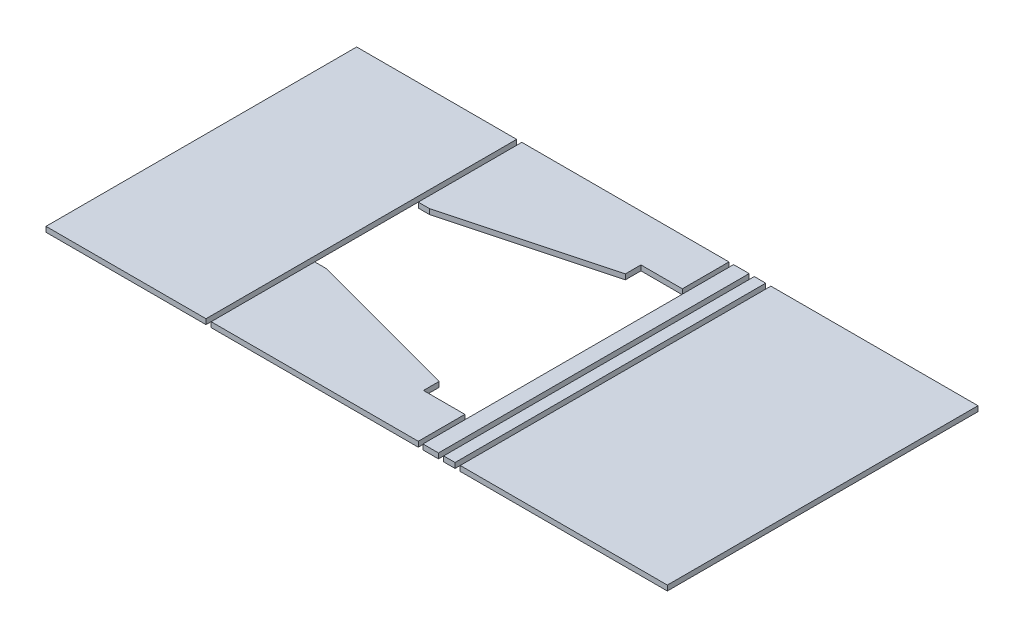
SolidWorks part; units mm, degrees
ref_plane "Front Plane" through (0, 0, 0) normal (0, 0, 1) x (1, 0, 0)
ref_plane "Top Plane" through (0, 0, 0) normal (0, 1, 0) x (1, 0, 0)
ref_plane "Right Plane" through (0, 0, 0) normal (1, 0, 0) x (0, 0, -1)
sketch "Sketch1" plane through (0, 0, 0) normal (0, 1, 0) x (1, 0, 0)
  line L0 (719, 90) -> (639, 90)
  line L33 (0, 0) -> (1200, 0)
  line L34 (0, 0) -> (0, 600)
  line L35 (0, 600) -> (1200, 600)
  line L36 (1200, 0) -> (1200, 600)
  line L37 (0, 0) -> (309, 0)
  line L38 (0, 0) -> (0, 600)
  line L39 (0, 600) -> (309, 600)
  line L40 (309, 0) -> (309, 600)
  line L41 (319, 600) -> (719, 600)
  line L42 (319, 600) -> (319, 400)
  line L43 (319, 400) -> (719, 400)
  line L44 (719, 600) -> (719, 400)
  line L45 (319, 0) -> (719, 0)
  line L46 (319, 0) -> (319, 200)
  line L47 (319, 200) -> (719, 200)
  line L48 (719, 0) -> (719, 200)
  line L49 (1200, 600) -> (800, 600)
  line L50 (1200, 600) -> (1200, 0)
  line L51 (1200, 0) -> (800, 0)
  line L52 (800, 600) -> (800, 0)
  line L53 (639, 90) -> (639, 120)
  line L54 (639, 120) -> (340.4359, 200)
  line L55 (719, 510) -> (639, 510)
  line L56 (790, 0) -> (768, 0)
  line L57 (790, 0) -> (790, 600)
  line L58 (790, 600) -> (768, 600)
  line L59 (768, 0) -> (768, 600)
  line L60 (758, 600) -> (728, 600)
  line L61 (758, 600) -> (758, 0)
  line L62 (758, 0) -> (728, 0)
  line L63 (728, 600) -> (728, 0)
  line L64 (639, 510) -> (639, 480)
  line L65 (639, 480) -> (340.4359, 400)
  dimension "D1" = 600
  dimension "D2" = 1200
  dimension "D3" = 309
  dimension "D4" = 200
  dimension "D5" = 200
  dimension "D6" = 10
  dimension "D7" = 10
  dimension "D8" = 400
  dimension "D9" = 400
  dimension "D10" = 400
  dimension "D11" = 15
  dimension "D12" = 80
  dimension "D13" = 30
  dimension "D14" = 90
  dimension "D15" = 10
  dimension "D16" = 22
  dimension "D17" = 10
  dimension "D18" = 30
  dimension "D19" = 90
  dimension "D20" = 30
  dimension "D21" = 15
  dimension "D22" = 80
extrude "Boss-Extrude1" add sketch "Sketch1" along normal blind 10 contours L33 L40 L35 L34 | L65 L64 L55 L44 L35 L42 L43 | L35 L52 L33 L36 | L53 L54 L47 L46 L33 L48 L0 | L59 L58 L57 L56 | L63 L62 L61 L60
